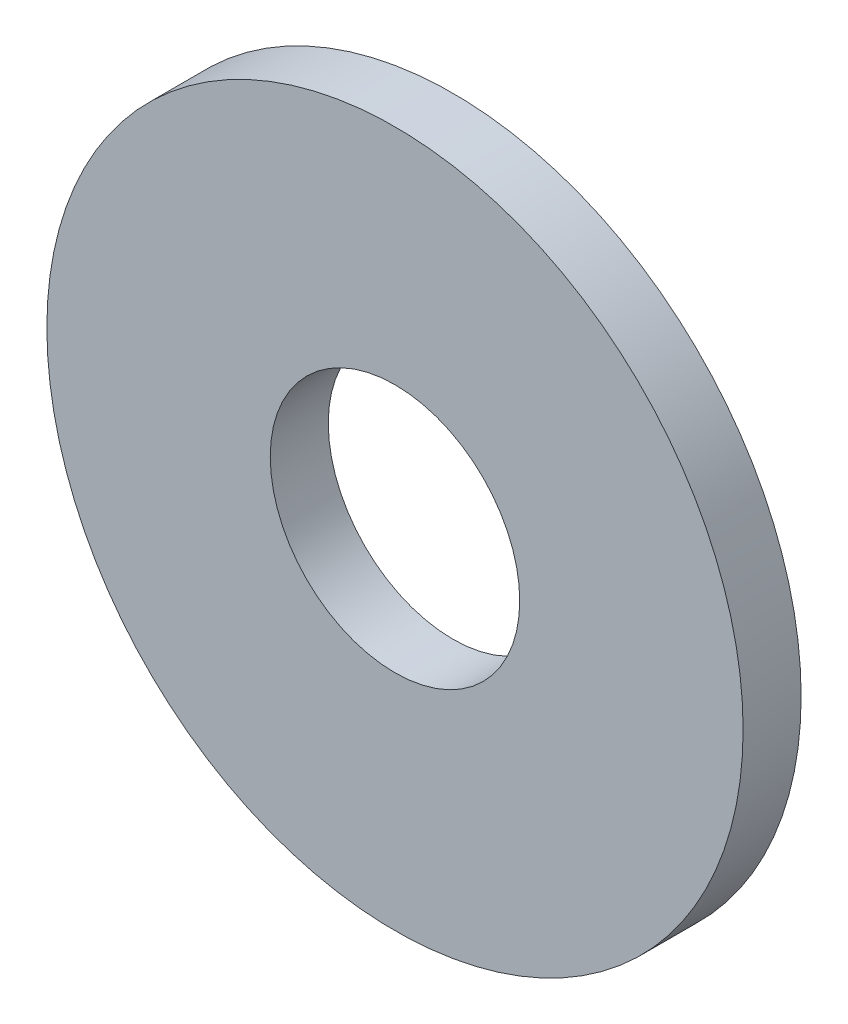
SolidWorks part; units mm, degrees
material "Plain Carbon Steel"
ref_plane "Front Plane" through (0, 0, 0) normal (0, 0, 1) x (1, 0, 0)
ref_plane "Top Plane" through (0, 0, 0) normal (0, 1, 0) x (1, 0, 0)
ref_plane "Right Plane" through (0, 0, 0) normal (1, 0, 0) x (0, 0, -1)
sketch "Sketch1" plane through (0, 0, 0) normal (0, 0, 1) x (1, 0, 0)
  circle A0 centre (0, 0) radius 6
  circle A1 centre (0, 0) radius 2.15
  dimension "D1" = 4.3
  dimension "D2" = 12
extrude "Boss-Extrude1" add sketch "Sketch1" along normal blind 1
